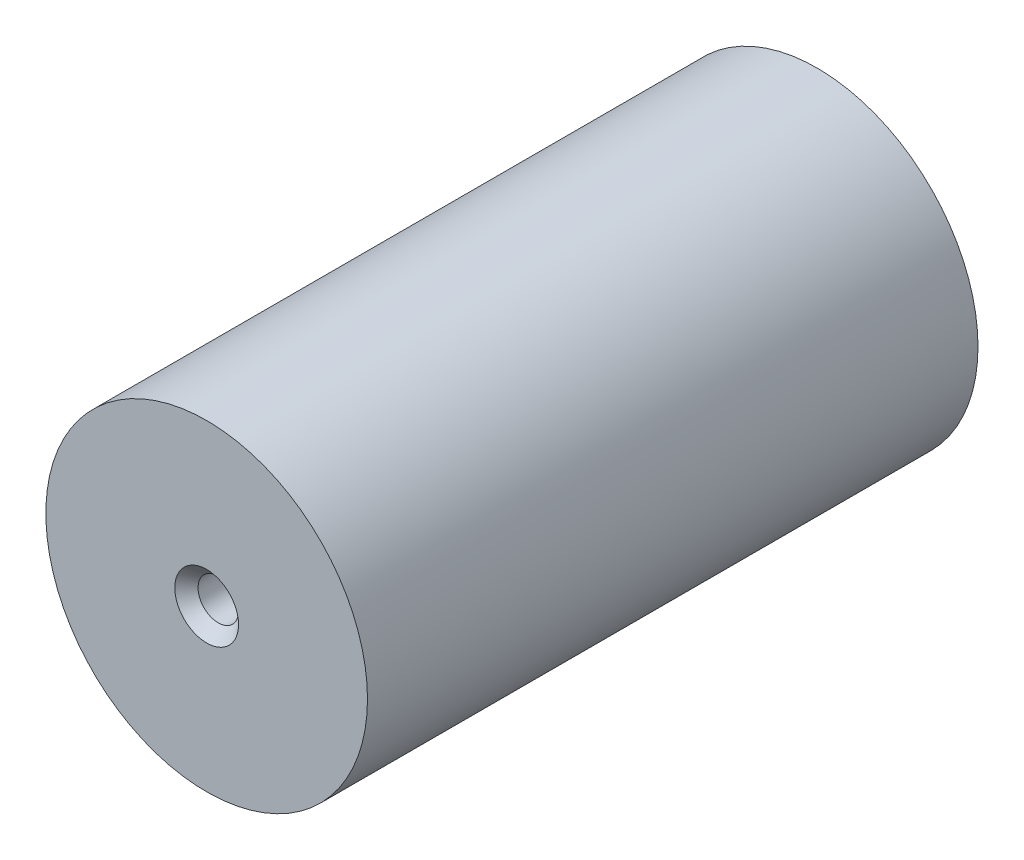
SolidWorks part; units mm, degrees
ref_plane "Front Plane" through (0, 0, 0) normal (0, 0, 1) x (1, 0, 0)
ref_plane "Top Plane" through (0, 0, 0) normal (0, 1, 0) x (1, 0, 0)
ref_plane "Right Plane" through (0, 0, 0) normal (1, 0, 0) x (0, 0, -1)
sketch "Sketch1" plane through (0, 0, 0) normal (0, 0, 1) x (1, 0, 0)
  circle A0 centre (0, 0) radius 13.716
  dimension "D1" = 27.432
extrude "Boss-Extrude1" add sketch "Sketch1" along normal blind 52.07
hole_wizard "#8-32 Tapped Hole1" positions "Sketch3" profile "Sketch2" tap size "#8-32" standard "ANSI Inch"
sketch "Sketch3" plane through (0, 0, 52.07) normal (0, 0, -1) x (-1, 0, 0)
  point P0 (0, 0)
sketch "Sketch2" plane through (0, 0, 52.07) normal (1, 0, 0) x (0, -1, 0)
  line L0 (0, 0) -> (0, 13.7378)
  line L1 (0, 13.7378) -> (1.7272, 12.7)
  line L2 (1.7272, 12.7) -> (1.7272, 0.9906)
  line L3 (1.7272, 0.9906) -> (2.7178, 0)
  line L5 (2.7178, 0) -> (0, 0)
  line L6 (-1.7272, 0.9906) -> (-2.7178, 0) construction
  line L10 (0, 13.7378) -> (-1.7272, 12.7) construction
  line L11 (0, -6.35) -> (0, 107.95) construction
  dimension "Tap Drill Dia." = 3.4544
  dimension "Tap Drill Depth" = 12.7
  dimension "Near C'Sink Dia." = 5.4356
  dimension "Near C'Sink Angle" = 90
  dimension "Drill Angle" = 118
cosmetic thread "Hole Thread1"
